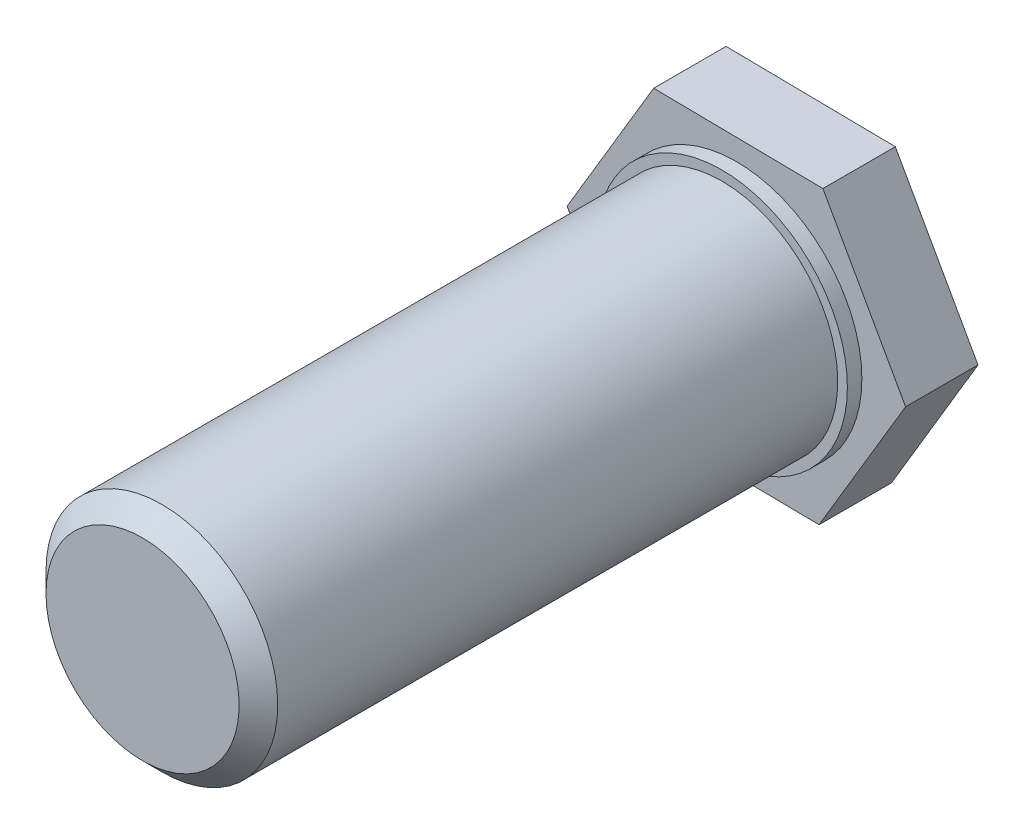
SolidWorks part; units mm, degrees
ref_plane "Front Plane" through (0, 0, 0) normal (0, 0, 1) x (1, 0, 0)
ref_plane "Top Plane" through (0, 0, 0) normal (0, 1, 0) x (1, 0, 0)
ref_plane "Right Plane" through (0, 0, 0) normal (1, 0, 0) x (0, 0, -1)
sketch "Sketch2" plane through (0, 0, 0) normal (0, 0, 1) x (1, 0, 0)
  line L1 (1.7929, 3.0127) -> (-1.7126, 3.059)
  line L2 (-1.7126, 3.059) -> (-3.5055, 0.0464)
  line L3 (-3.5055, 0.0464) -> (-1.7929, -3.0127)
  line L4 (-1.7929, -3.0127) -> (1.7126, -3.059)
  line L5 (1.7126, -3.059) -> (3.5055, -0.0464)
  line L6 (3.5055, -0.0464) -> (1.7929, 3.0127)
  circle A0 centre (0, 0) radius 3.0361 construction
extrude "Boss-Extrude6" add sketch "Sketch2" along normal blind 1.5
sketch "Sketch4" plane through (0, 0, 1.5) normal (0, 0, 1) x (1, 0, 0)
  circle A0 centre (0, 0) radius 2.6
extrude "Boss-Extrude7" add sketch "Sketch4" along normal blind 0.3
sketch "Sketch5" plane through (0, 0, 1.8) normal (0, 0, 1) x (1, 0, 0)
  circle A0 centre (0, 0) radius 2.4
extrude "Boss-Extrude10" add sketch "Sketch5" along normal blind 12
chamfer "Chamfer3" distance 0.4 angle 45 1 edges at (2.4, 0, 13.8)
sketch "Sketch7" plane through (0, 0, 13.8) normal (0, 0, 1) x (1, 0, 0)
  circle A0 centre (0, 0) radius 2.4
curve "Helix/Spiral2" pitch 0.25 height 10 turns 40
